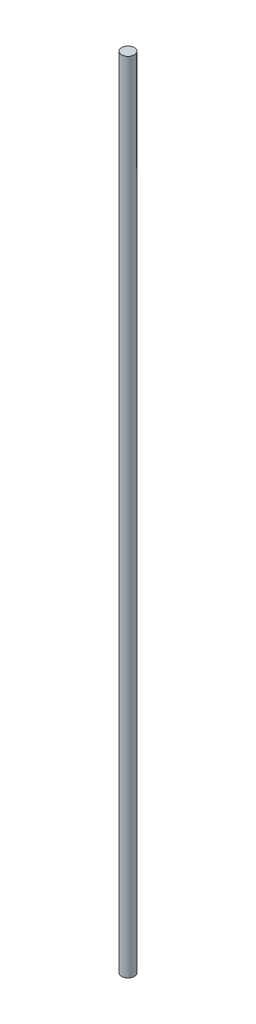
SolidWorks part; units mm, degrees
ref_plane "Front Plane" through (0, 0, 0) normal (0, 0, 1) x (1, 0, 0)
ref_plane "Top Plane" through (0, 0, 0) normal (0, 1, 0) x (1, 0, 0)
ref_plane "Right Plane" through (0, 0, 0) normal (1, 0, 0) x (0, 0, -1)
sketch "Sketch1" plane through (0, 0, 0) normal (0, 1, 0) x (1, 0, 0)
  circle A0 centre (0, 0) radius 6
  dimension "D1" = 12
extrude "Boss-Extrude1" add sketch "Sketch1" along normal blind 755
